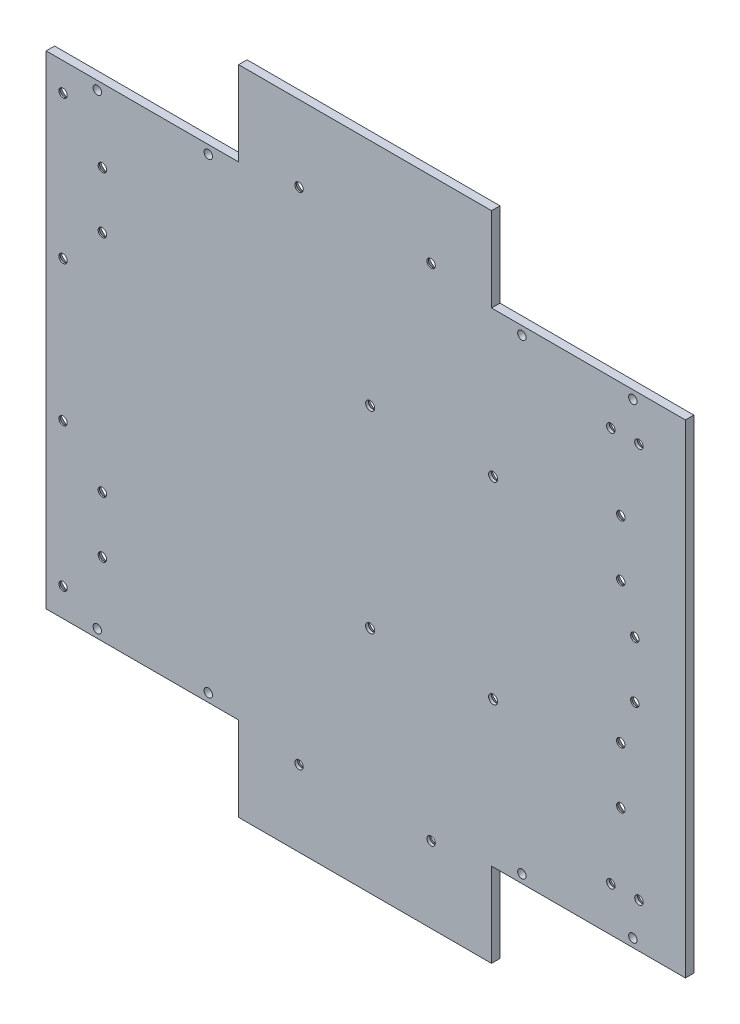
SolidWorks part; units mm, degrees
ref_plane "Front" through (0, 0, 0) normal (0, 0, 1) x (1, 0, 0)
ref_plane "Top" through (0, 0, 0) normal (0, 1, 0) x (1, 0, 0)
ref_plane "Right" through (0, 0, 0) normal (1, 0, 0) x (0, 0, -1)
sketch "草图1" plane through (0, 0, 0) normal (0, 0, 1) x (1, 0, 0)
  line L0 (-105.75, 86) -> (-105.75, 70)
  line L1 (-105.75, 86) -> (105.75, 86)
  line L2 (-105.75, 70) -> (-105.75, -86)
  line L3 (-105.75, -86) -> (105.75, -86)
  line L4 (105.75, 86) -> (105.75, -86)
  line L6 (-105.75, -86) -> (-75.75, -61.6028) construction
  line L7 (-129.21, 0) -> (-105.75, 0) construction
  line L43 (-58.101, -47.25) -> (-49.186, -40) construction
  line L48 (105.75, 0) -> (147.9998, 0) construction
  point P0 (0, 0)
extrude "凸台-拉伸1" add sketch "草图1" along normal blind 3
sketch "草图2" plane through (0, 0, 3) normal (0, 0, 1) x (1, 0, 0)
  line L0 (-171.9725, 0) -> (177.2997, 0) construction
  circle A0 centre (97.05, 83) radius 1.5
  circle A1 centre (-93.55, 83) radius 1.5
  circle A2 centre (57.55, 83) radius 1.5
  circle A3 centre (-54.05, 83) radius 1.5
  circle A4 centre (57.55, -83) radius 1.5
  circle A5 centre (97.05, -83) radius 1.5
  circle A6 centre (-54.05, -83) radius 1.5
  circle A7 centre (-93.55, -83) radius 1.5
extrude "切除-拉伸1" cut sketch "草图2" against normal blind 10
sketch "草图3" plane through (0, 0, 3) normal (0, 0, 1) x (1, 0, 0)
  line L0 (105.75, 86) -> (115.75, 86)
  line L1 (115.75, 86) -> (115.75, -86)
  line L2 (115.75, -86) -> (105.75, -86)
  line L3 (105.75, -86) -> (105.75, 86)
  line L4 (-43.25, 83) -> (46.75, 83)
  line L5 (-43.25, 83) -> (-43.25, 116)
  line L6 (-43.25, 116) -> (46.75, 116)
  line L7 (46.75, 116) -> (46.75, 83)
  line L8 (-153.596, 0) -> (171.6121, 0) construction
  line L9 (-43.25, -83) -> (46.75, -83)
  line L10 (46.75, -116) -> (46.75, -83)
  line L11 (-43.25, -83) -> (-43.25, -116)
  line L12 (-43.25, -116) -> (46.75, -116)
extrude "凸台-拉伸2" add sketch "草图3" against normal blind 3
sketch "草图4" plane through (0, 0, 3) normal (0, 0, 1) x (1, 0, 0)
  line L0 (-148.4712, 0) -> (147.7719, 0) construction
  circle A7 centre (3.55, 34.3) radius 1.6
  circle A8 centre (47.31, 34.3) radius 1.6
  circle A9 centre (47.31, -34.3) radius 1.6
  circle A10 centre (3.55, -34.3) radius 1.6
extrude "切除-拉伸2" cut sketch "草图4" against normal blind 10
sketch "草图5" plane through (0, 0, 3) normal (0, 0, 1) x (1, 0, 0)
  circle A3 centre (92.75, 45) radius 1.5
  circle A4 centre (92.75, 25) radius 1.5
  circle A5 centre (92.75, -25) radius 1.5
  circle A6 centre (92.75, -45) radius 1.5
extrude "切除-拉伸3" cut sketch "草图5" against normal blind 10
sketch "草图6" plane through (0, 0, 3) normal (0, 0, 1) x (1, 0, 0)
  line L0 (-159.5225, 0) -> (158.0171, 0) construction
  circle A0 centre (25.25, -89) radius 1.5
  circle A1 centre (-21.75, 89) radius 1.5
  circle A2 centre (25.25, 89) radius 1.5
  circle A3 centre (-21.75, -89) radius 1.5
extrude "切除-拉伸4" cut sketch "草图6" against normal blind 10
sketch "草图7" plane through (0, 0, 0) normal (0, 0, -1) x (-1, 0, 0)
  circle A3 centre (91.75, -60) radius 1.5
  circle A4 centre (91.75, -40) radius 1.5
  circle A5 centre (91.75, 60) radius 1.5
  circle A6 centre (91.75, 40) radius 1.5
extrude "切除-拉伸5" cut sketch "草图7" against normal blind 74
sketch "草图8" plane through (0, 0, 0) normal (0, 0, -1) x (-1, 0, 0)
  circle A1 centre (-97.75, 10) radius 1.5
  circle A2 centre (-97.75, -10) radius 1.5
extrude "切除-拉伸6" cut sketch "草图8" against normal blind 10
sketch "草图9" plane through (0, 0, 0) normal (0, 0, -1) x (-1, 0, 0)
  line L0 (105.75, 86) -> (111.75, 86)
  line L1 (111.75, 86) -> (111.75, -86)
  line L2 (111.75, -86) -> (105.75, -86)
  line L3 (105.75, -86) -> (105.75, 86)
extrude "凸台-拉伸3" add sketch "草图9" against normal blind 3
sketch "草图10" plane through (0, 0, 0) normal (0, 0, -1) x (-1, 0, 0)
  circle A2 centre (105.75, 76) radius 1.5
  circle A3 centre (105.75, 25) radius 1.5
  circle A4 centre (105.75, -25) radius 1.5
  circle A5 centre (105.75, -76) radius 1.5
extrude "切除-拉伸7" cut sketch "草图10" against normal blind 15
chamfer "倒角2" distance 2.5 angle 45 1 edges at (26.75, 89, 0)
chamfer "倒角3" distance 2.5 angle 45 9 edges at (-107.25, -76, 0) (-93.25, -60, 0) (-93.25, -40, 0) (-107.25, -25, 0) (-107.25, 25, 0) (-93.25, 40, 0) (-93.25, 60, 0) (-107.25, 76, 0) (-20.25, 89, 0)
chamfer "倒角5" distance 2.5 angle 45 6 edges at (94.25, 25, 0) (94.25, 45, 0) (96.25, 10, 0) (96.25, -10, 0) (94.25, -25, 0) (94.25, -45, 0)
sketch "草图11" plane through (0, 0, 0) normal (0, 0, -1) x (-1, 0, 0)
  circle A0 centre (-89.2092, 70.25) radius 1.5
  circle A1 centre (-99.2092, 70.25) radius 1.5
extrude "切除-拉伸8" cut sketch "草图11" against normal blind 10
mirror "镜向2" about plane through (0, 0, 0) normal (0, 1, 0) of "切除-拉伸8"
chamfer "倒角6" distance 2 angle 45 1 edges at (48.91, 34.3, 0)
chamfer "倒角7" distance 2 angle 45 7 edges at (97.7092, 70.25, 0) (87.7092, 70.25, 0) (97.7092, -70.25, 0) (87.7092, -70.25, 0) (48.91, -34.3, 0) (5.15, -34.3, 0) (5.15, 34.3, 0)
chamfer "倒角8" distance 2 angle 45 2 edges at (-20.25, -89, 0) (26.75, -89, 0)
mirror "镜向1" about plane through (0, 0, 0) normal (0, 1, 0)
